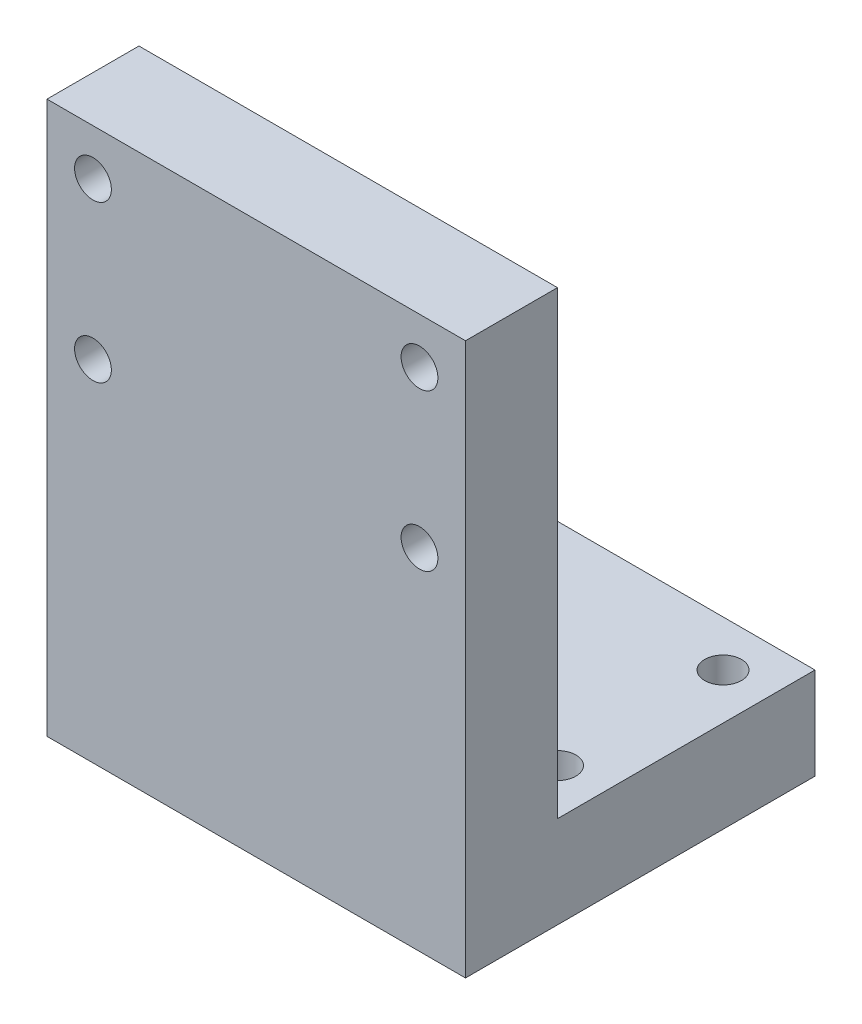
SolidWorks part; units mm, degrees
ref_plane "Front Plane" through (0, 0, 0) normal (0, 0, 1) x (1, 0, 0)
ref_plane "Top Plane" through (0, 0, 0) normal (0, 1, 0) x (1, 0, 0)
ref_plane "Right Plane" through (0, 0, 0) normal (1, 0, 0) x (0, 0, -1)
sketch "Sketch1" plane through (0, 0, 0) normal (0, 1, 0) x (1, 0, 0)
  line L0 (-22.75, 14) -> (0, 14)
  line L1 (-22.75, 14) -> (-22.75, -14)
  line L2 (-22.75, -14) -> (22.75, -14)
  line L3 (22.75, 14) -> (22.75, -14)
  line L4 (0, 14) -> (22.75, 14)
  line L5 (0, 14) -> (0, -14) construction
  line L6 (-22.75, 0) -> (22.75, 0) construction
  line L7 (-17.75, 9) -> (-17.75, -9) construction
  line L8 (-17.75, -9) -> (17.75, -9) construction
  line L9 (17.75, -9) -> (17.75, 9) construction
  line L10 (17.75, 9) -> (-17.75, 9) construction
  circle A0 centre (-17.75, 9) radius 2
  circle A1 centre (-17.75, -9) radius 2
  circle A2 centre (17.75, 9) radius 2
  circle A3 centre (17.75, -9) radius 2
  point P17 (0, 0)
  dimension "D3" = 4
  dimension "D5" = 4
  dimension "D6" = 4
  dimension "D7" = 4
  dimension "D9" = 5
  dimension "D10" = 5
  dimension "D1" = 45.5
  dimension "D2" = 28
  dimension "D4" = 18
  dimension "D8" = 35.5
extrude "Base Extrusion" add sketch "Sketch1" along normal blind 10
sketch "Sketch2" plane through (0, 0, 0) normal (0, -1, 0) x (1, 0, 0)
  line L0 (0, 14) -> (0, -14) construction
  line L1 (-22.75, 14) -> (22.75, 14) construction
  line L2 (22.75, -14) -> (-22.75, -14) construction
  circle A0 centre (-17.75, 9) radius 3
  circle A1 centre (-17.75, -9) radius 3
  circle A2 centre (17.75, -9) radius 3
  circle A3 centre (17.75, 9) radius 3
  dimension "D1" = 6
  dimension "D2" = 6
extrude "First Base Holes" cut sketch "Sketch2" against normal blind 6
sketch "Sketch5" plane through (0, 0, 0) normal (0, 1, 0) x (1, 0, 0)
  line L0 (-22.75, -14) -> (22.75, -14)
  line L1 (22.75, -14) -> (22.75, -24)
  line L2 (22.75, -24) -> (-22.75, -24)
  line L3 (-22.75, -24) -> (-22.75, -14)
  dimension "D1" = 10
extrude "Boss-Extrude3" add sketch "Sketch5" along normal blind 60
sketch "Sketch6" plane through (0, 0, 14) normal (0, 0, -1) x (-1, 0, 0)
  line L0 (-22.75, 60) -> (22.75, 60)
  line L1 (-22.75, 60) -> (-22.75, 33)
  line L2 (-22.75, 33) -> (22.75, 33)
  line L3 (22.75, 60) -> (22.75, 33)
  line L4 (22.75, 60) -> (16.5851, 60)
  line L5 (-17.75, 55) -> (-17.75, 38) construction
  line L6 (-17.75, 38) -> (17.75, 38) construction
  line L7 (17.75, 38) -> (17.75, 55) construction
  line L8 (17.75, 55) -> (-17.75, 55) construction
  circle A0 centre (-17.75, 55) radius 2
  circle A1 centre (-17.75, 38) radius 2
  circle A2 centre (17.75, 55) radius 2
  circle A3 centre (17.75, 38) radius 2
  point P13 (-22.75, 60)
  dimension "D3" = 4
  dimension "D5" = 4
  dimension "D6" = 4
  dimension "D7" = 4
  dimension "D9" = 5
  dimension "D10" = 5
  dimension "D1" = 45.5
  dimension "D2" = 27
  dimension "D4" = 17
  dimension "D8" = 35.5
extrude "Cut-Extrude2" cut sketch "Sketch6" against normal up to next contours A0 | A1 | A3 | A2
sketch "Sketch7" plane through (0, 0, 14) normal (0, 0, -1) x (-1, 0, 0)
  line L0 (0, 60) -> (0, 15.0631) construction
  line L1 (-22.75, 60) -> (22.75, 60) construction
  circle A0 centre (-17.75, 55) radius 3
  circle A1 centre (-17.75, 38) radius 3
  circle A2 centre (17.75, 38) radius 3
  circle A3 centre (17.75, 55) radius 3
  dimension "D1" = 6
  dimension "D2" = 6
extrude "Cut-Extrude3" cut sketch "Sketch7" against normal blind 6
